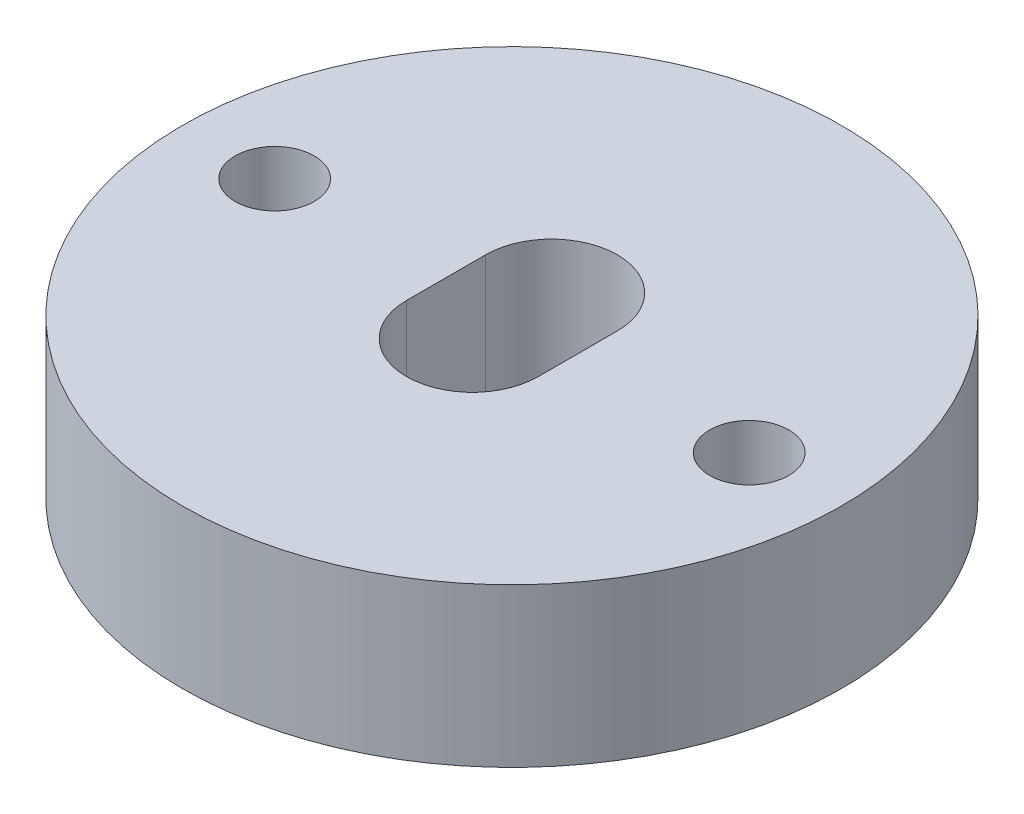
SolidWorks part; units mm, degrees
ref_plane "Front Plane" through (0, 0, 0) normal (0, 0, 1) x (1, 0, 0)
ref_plane "Top Plane" through (0, 0, 0) normal (0, 1, 0) x (1, 0, 0)
ref_plane "Right Plane" through (0, 0, 0) normal (1, 0, 0) x (0, 0, -1)
sketch "Sketch1" plane through (0, 0, 0) normal (0, 1, 0) x (1, 0, 0)
  circle A0 centre (0, 0) radius 12.5
  dimension "D1" = 25
extrude "Boss-Extrude1" add sketch "Sketch1" along normal blind 6
sketch "Sketch2" plane through (0, 6, 0) normal (0, 1, 0) x (1, 0, 0)
  line L0 (0, -1.5) -> (0, 1.5) construction
  line L1 (-2.5, -1.5) -> (-2.5, 1.5)
  line L2 (2.5, -1.5) -> (2.5, 1.5)
  arc A0 (-2.5, -1.5) -> (2.5, -1.5) centre (0, -1.5) ccw
  arc A1 (2.5, 1.5) -> (-2.5, 1.5) centre (0, 1.5) ccw
  point P2 (0, 0)
  dimension "D1" = 2.5
  dimension "D2" = 3
extrude "Cut-Extrude1" cut sketch "Sketch2" against normal through all
sketch "Sketch3" plane through (0, 6, 0) normal (0, 1, 0) x (1, 0, 0)
  line L0 (0, 12.5) -> (0, -12.5) construction
  circle A0 centre (-9, 0) radius 1.5
  circle A1 centre (0, 0) radius 12.5 construction
  circle A2 centre (9, 0) radius 1.5
  dimension "D1" = 3
  dimension "D2" = 9
extrude "Cut-Extrude2" cut sketch "Sketch3" against normal through all
